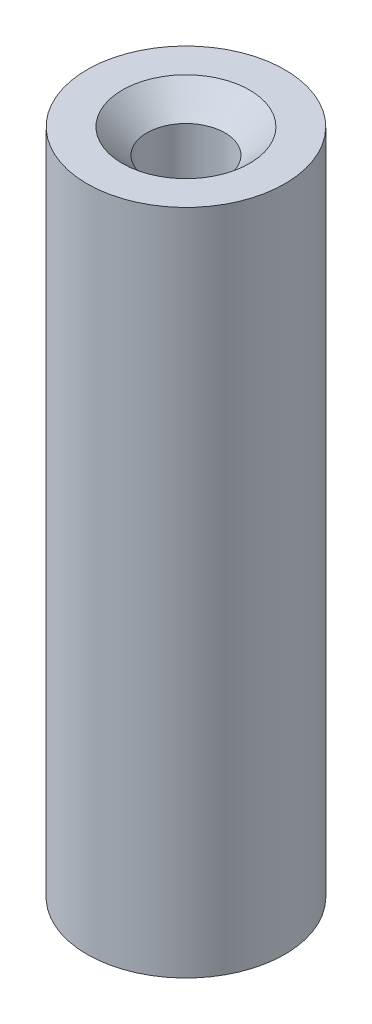
SolidWorks part; units mm, degrees
ref_plane "Ebene vorne" through (0, 0, 0) normal (0, 0, 1) x (1, 0, 0)
ref_plane "Ebene oben" through (0, 0, 0) normal (0, 1, 0) x (1, 0, 0)
ref_plane "Ebene rechts" through (0, 0, 0) normal (1, 0, 0) x (0, 0, -1)
sketch "Skizze1" plane through (0, 0, 0) normal (0, 1, 0) x (1, 0, 0)
  circle A0 centre (0, 0) radius 4
  circle A1 centre (0, 0) radius 1.575
  dimension "D1" = 8
  dimension "D2" = 3.15
extrude "Aufsatz-Linear austragen1" add sketch "Skizze1" along normal blind 27
chamfer "Fase1" distance 1 angle 45 2 edges at (0, 0, 1.575) (0, 27, 1.575)
